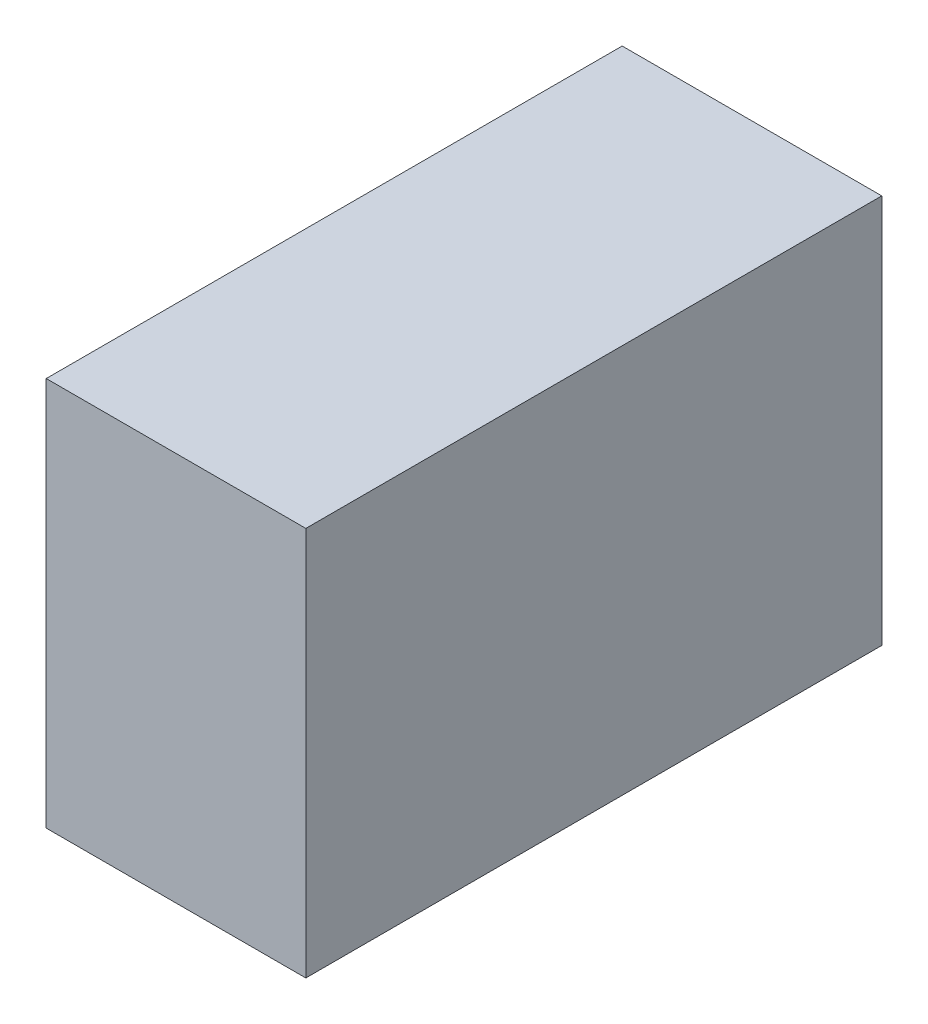
SolidWorks part; units mm, degrees
ref_plane "Front Plane" through (0, 0, 0) normal (0, 0, 1) x (1, 0, 0)
ref_plane "Top Plane" through (0, 0, 0) normal (0, 1, 0) x (1, 0, 0)
ref_plane "Right Plane" through (0, 0, 0) normal (1, 0, 0) x (0, 0, -1)
sketch "Sketch1" plane through (0, 0, 0) normal (0, 1, 0) x (1, 0, 0)
  line L1 (0, 0) -> (50.8, 0)
  line L2 (0, 0) -> (0, 112.7125)
  line L3 (0, 112.7125) -> (50.8, 112.7125)
  line L4 (50.8, 0) -> (50.8, 112.7125)
  dimension "D1" = 50.8
  dimension "D2" = 112.7125
extrude "Boss-Extrude1" add sketch "Sketch1" along normal blind 76.2
equation "\"D2@Sketch1\"=4+(7/16)"
